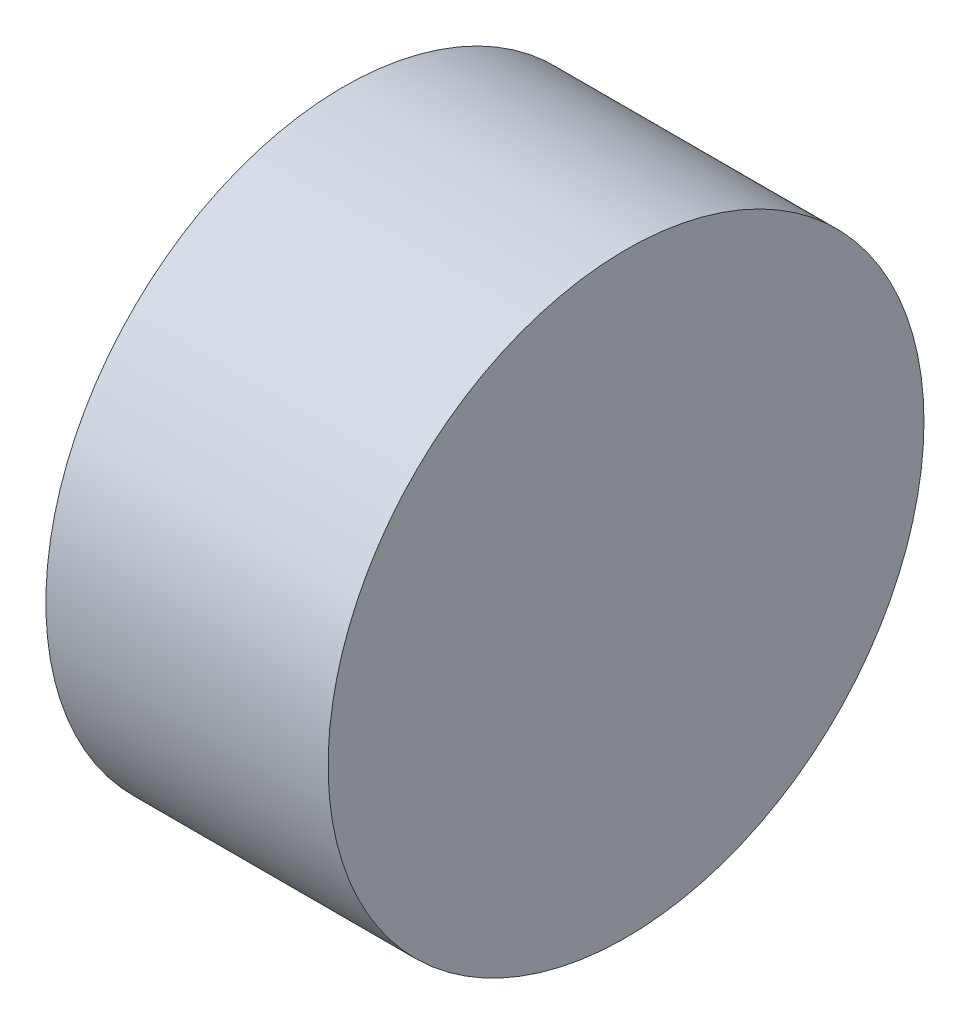
SolidWorks part; units mm, degrees
ref_plane "Front Plane" through (0, 0, 0) normal (0, 0, 1) x (1, 0, 0)
ref_plane "Top Plane" through (0, 0, 0) normal (0, 1, 0) x (1, 0, 0)
ref_plane "Right Plane" through (0, 0, 0) normal (1, 0, 0) x (0, 0, -1)
other "Graphic1"
sketch "Sketch1" plane through (0, 0, 0) normal (1, 0, 0) x (0, 0, -1)
  circle A0 centre (0, 0) radius 0.038
extrude "Boss-Extrude1" add sketch "Sketch1" along normal blind 0.036
